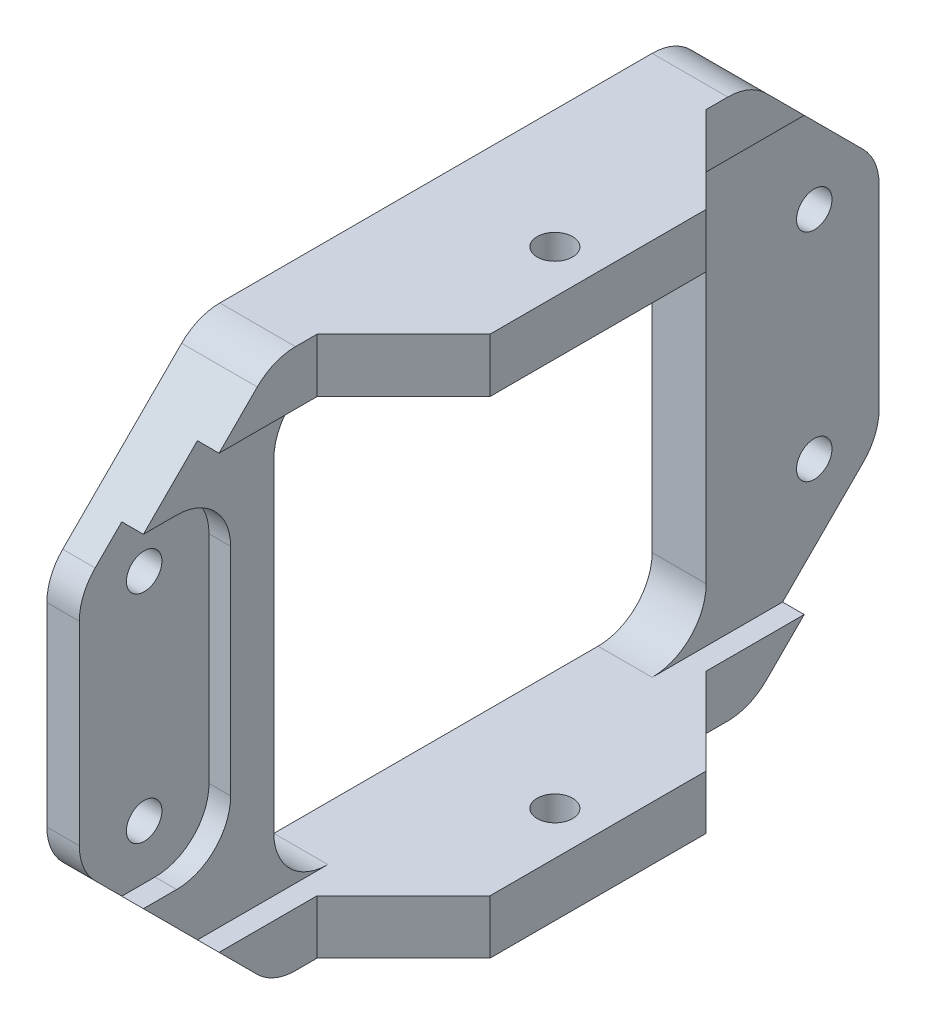
SolidWorks part; units mm, degrees
ref_plane "Front Plane" through (0, 0, 0) normal (0, 0, 1) x (1, 0, 0)
ref_plane "Top Plane" through (0, 0, 0) normal (0, 1, 0) x (1, 0, 0)
ref_plane "Right Plane" through (0, 0, 0) normal (1, 0, 0) x (0, 0, -1)
sketch "Sketch1" plane through (0, 0, 0) normal (1, 0, 0) x (0, 0, -1)
  line L0 (0, 0) -> (38.1, 0) construction
  line L1 (38.1, -12.7) -> (38.1, 12.7) construction
  line L2 (-25.4, 31.75) -> (25.4, 31.75)
  line L3 (29.8901, 29.8901) -> (43.8601, 15.9201)
  line L4 (45.72, 11.43) -> (45.72, -11.43)
  line L5 (-19.05, 25.4) -> (19.05, 25.4)
  line L6 (25.4, 19.05) -> (25.4, -19.05)
  line L7 (-19.05, -25.4) -> (19.05, -25.4)
  line L8 (-25.4, -31.75) -> (25.4, -31.75)
  line L9 (29.8901, -29.8901) -> (43.8601, -15.9201)
  line L10 (0, 0) -> (0, 19.05) construction
  line L11 (-38.1, -12.7) -> (-38.1, 12.7) construction
  line L12 (-29.8901, -29.8901) -> (-43.8601, -15.9201)
  line L13 (-25.4, 19.05) -> (-25.4, -19.05)
  line L14 (-45.72, 11.43) -> (-45.72, -11.43)
  line L15 (-29.8901, 29.8901) -> (-43.8601, 15.9201)
  circle A0 centre (38.1, 12.7) radius 2.0828
  circle A1 centre (0, 0) radius 19.05 construction
  arc A2 (45.72, 11.43) -> (43.8601, 15.9201) centre (39.37, 11.43) ccw
  arc A3 (29.8901, 29.8901) -> (25.4, 31.75) centre (25.4, 25.4) ccw
  arc A4 (25.4, 19.05) -> (19.05, 25.4) centre (19.05, 19.05) ccw
  arc A5 (25.4, -19.05) -> (19.05, -25.4) centre (19.05, -19.05) cw
  arc A6 (29.8901, -29.8901) -> (25.4, -31.75) centre (25.4, -25.4) cw
  arc A7 (45.72, -11.43) -> (43.8601, -15.9201) centre (39.37, -11.43) cw
  circle A8 centre (38.1, -12.7) radius 2.0828
  circle A9 centre (-38.1, -12.7) radius 2.0828
  arc A10 (-45.72, -11.43) -> (-43.8601, -15.9201) centre (-39.37, -11.43) ccw
  arc A11 (-29.8901, -29.8901) -> (-25.4, -31.75) centre (-25.4, -25.4) ccw
  arc A12 (-25.4, -19.05) -> (-19.05, -25.4) centre (-19.05, -19.05) ccw
  arc A13 (-25.4, 19.05) -> (-19.05, 25.4) centre (-19.05, 19.05) cw
  arc A14 (-29.8901, 29.8901) -> (-25.4, 31.75) centre (-25.4, 25.4) cw
  arc A15 (-45.72, 11.43) -> (-43.8601, 15.9201) centre (-39.37, 11.43) cw
  circle A16 centre (-38.1, 12.7) radius 2.0828
  point P6 (-25.4, 0)
  point P8 (0, 31.75)
  point P13 (45.72, 0)
  point P22 (0, 25.4)
  point P24 (0, -25.4)
  point P35 (25.4, 0)
  point P55 (0, -31.75)
  point P56 (-45.72, 0)
  dimension "D1" = 38.1
  dimension "D3" = 4.1656
  dimension "D4" = 38.1
  dimension "D9" = 6.35
  dimension "D2" = 12.7
  dimension "D5" = 45
  dimension "D6" = 6.35
  dimension "D7" = 31.75
  dimension "D8" = 6.35
  dimension "D10" = 7.62
  dimension "D11" = 19.05
  dimension "D12" = 19.05
extrude "Boss-Extrude1" add sketch "Sketch1" along normal blind 6.35
sketch "Sketch2" plane through (6.35, 0, 0) normal (1, 0, 0) x (0, 0, -1)
  line L0 (25.4, 31.75) -> (-25.4, 31.75) construction
  line L1 (19.05, 25.4) -> (-19.05, 25.4) construction
  line L2 (25.4, 31.75) -> (-25.4, 31.75)
  line L3 (19.05, 25.4) -> (-19.05, 25.4)
  line L4 (-29.8901, 29.8901) -> (-43.8601, 15.9201) construction
  line L5 (-29.8901, 29.8901) -> (-34.3803, 25.4)
  line L6 (-19.05, 25.4) -> (-34.3803, 25.4)
  line L7 (43.8601, 15.9201) -> (29.8901, 29.8901) construction
  line L8 (34.3803, 25.4) -> (29.8901, 29.8901)
  line L9 (19.05, 25.4) -> (34.3803, 25.4)
  arc A0 (-25.4, 31.75) -> (-29.8901, 29.8901) centre (-25.4, 25.4) ccw construction
  arc A1 (-25.4, 31.75) -> (-29.8901, 29.8901) centre (-25.4, 25.4) ccw
  arc A2 (29.8901, 29.8901) -> (25.4, 31.75) centre (25.4, 25.4) ccw construction
  arc A3 (29.8901, 29.8901) -> (25.4, 31.75) centre (25.4, 25.4) ccw
extrude "Boss-Extrude2" add sketch "Sketch2" along normal blind 12.7
mirror "Mirror1" about plane through (0, 0, 0) normal (0, 1, 0) of "Boss-Extrude2"
sketch "Sketch3" plane through (0, -31.75, 0) normal (0, -1, 0) x (1, 0, 0)
  line L0 (19.05, -34.3803) -> (6.35, -34.3803) construction
  line L1 (19.05, 34.3803) -> (6.35, 34.3803) construction
  line L2 (19.05, -34.3803) -> (6.35, -34.3803)
  line L3 (19.05, 34.3803) -> (6.35, 34.3803)
  line L4 (19.05, 34.3803) -> (19.05, 12.7) construction
  line L5 (19.05, 0) -> (6.35, 0) construction
  line L6 (19.05, 12.7) -> (8.89, 22.86)
  line L8 (19.05, 34.3803) -> (19.05, 12.7)
  line L11 (19.05, -12.7) -> (19.05, 0)
  line L13 (19.05, 0) -> (19.05, -34.3803) construction
  line L14 (8.89, 34.3803) -> (8.89, 22.86)
  line L15 (19.05, -12.7) -> (8.89, -22.86)
  line L16 (8.89, -34.3803) -> (8.89, -22.86)
  line L17 (19.05, -12.7) -> (19.05, -34.3803)
  circle A0 centre (13.97, 0) radius 2.0828
  line M8 (0, -25.4) -> (19.05, -25.4)
  line M9 (19.05, -25.4) -> (19.05, 25.4)
  line M10 (19.05, 25.4) -> (0, 25.4)
  dimension "D4" = 5.08
  dimension "D5" = 4.1656
  dimension "D1" = 2.54
  dimension "D2" = 12.7
  dimension "D3" = 45
extrude "Cut-Extrude2" cut sketch "Sketch3" against normal through all contours L3 L14 L8 M10 | L14 L6 M10 M9 | L17 L16 L2 M8 | L16 L15 M8 M9 | A0
sketch "Sketch5" plane through (6.35, 0, 0) normal (1, 0, 0) x (0, 0, -1)
  line L0 (-45.72, 11.43) -> (-45.72, -11.43) construction
  line L1 (-36.83, 19.05) -> (-45.72, 19.05)
  line L2 (-30.48, 12.7) -> (-30.48, -12.7)
  line L3 (-36.83, -19.05) -> (-45.72, -19.05)
  line L4 (-45.72, 19.05) -> (-45.72, -19.05)
  arc A0 (-36.83, -19.05) -> (-30.48, -12.7) centre (-36.83, -12.7) ccw
  arc A1 (-30.48, 12.7) -> (-36.83, 19.05) centre (-36.83, 12.7) ccw
  point P6 (-30.48, 0)
  dimension "D3" = 6.35
  dimension "D1" = 15.24
  dimension "D2" = 38.1
extrude "Cut-Extrude3" cut sketch "Sketch5" against normal blind 2.54
